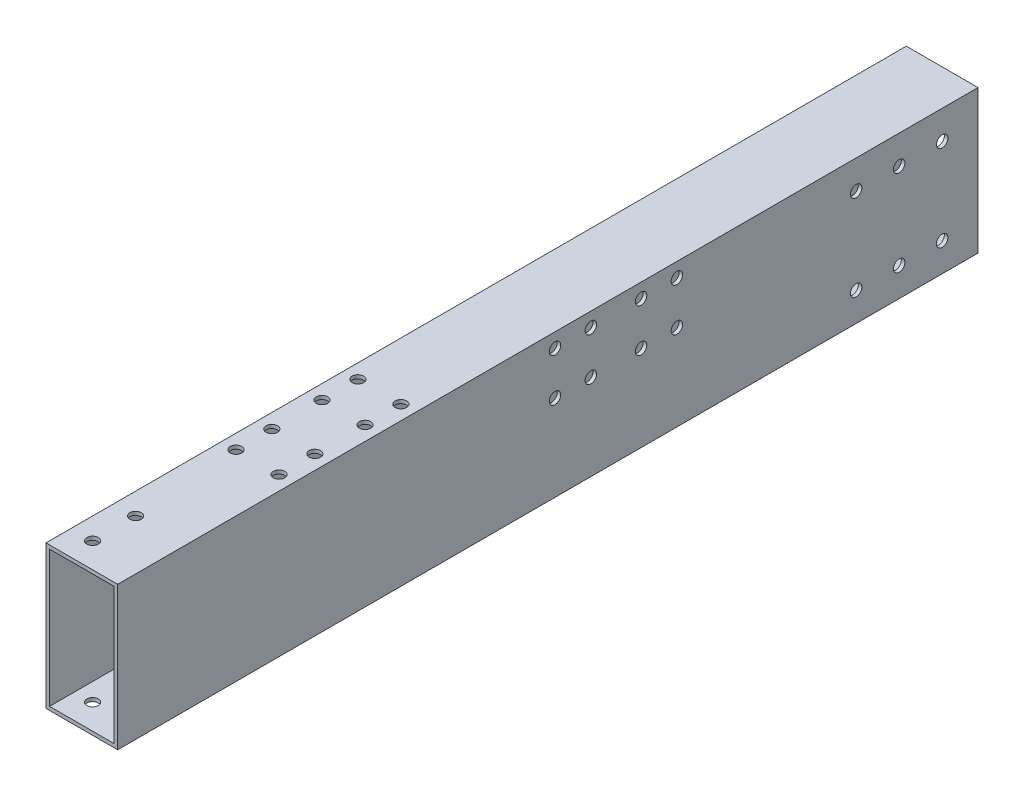
SolidWorks part; units mm, degrees
material "1060-O (SS)"
ref_plane "前视基准面" through (0, 0, 0) normal (0, 0, 1) x (1, 0, 0)
ref_plane "上视基准面" through (0, 0, 0) normal (0, 1, 0) x (1, 0, 0)
ref_plane "右视基准面" through (0, 0, 0) normal (1, 0, 0) x (0, 0, -1)
other "Configuration Table"
sketch "草图1" plane through (0, 0, 0) normal (0, 0, 1) x (1, 0, 0)
  line L1 (0, 0) -> (20, 0)
  line L2 (0, 0) -> (0, 40)
  line L3 (0, 40) -> (20, 40)
  line L4 (20, 0) -> (20, 40)
  line L5 (1, 1) -> (19, 1)
  line L6 (1, 1) -> (1, 39)
  line L7 (1, 39) -> (19, 39)
  line L8 (19, 1) -> (19, 39)
  dimension "D1" = 20
  dimension "D2" = 40
  dimension "D3" = 1
  dimension "D4" = 1
  dimension "D5" = 1
  dimension "D6" = 1
extrude "凸台-拉伸1" add sketch "草图1" along normal blind 240
sketch "草图2" plane through (0, 40, 0) normal (0, 1, 0) x (1, 0, 0)
  circle A1 centre (6, -221) radius 1.6
  circle A2 centre (6, -221) radius 1.6
  circle A3 centre (6, -233) radius 1.6
  circle A4 centre (6, -233) radius 1.6
  circle A21 centre (34, -221) radius 1.6
  circle A22 centre (34, -221) radius 1.6
  circle A23 centre (34, -233) radius 1.6
  circle A24 centre (34, -233) radius 1.6
  circle A25 centre (4, -191) radius 1.6
  circle A30 centre (4, -191) radius 1.6
  circle A31 centre (4, -181) radius 1.6
  circle A32 centre (4, -181) radius 1.6
  circle A33 centre (16, -167) radius 1.6
  circle A34 centre (16, -167) radius 1.6
  circle A35 centre (16, -157) radius 1.6
  circle A36 centre (16, -157) radius 1.6
  circle A37 centre (4, -167) radius 1.6
  circle A38 centre (4, -167) radius 1.6
  circle A39 centre (4, -157) radius 1.6
  circle A40 centre (4, -157) radius 1.6
  circle A41 centre (16, -191) radius 1.6
  circle A42 centre (16, -191) radius 1.6
  circle A43 centre (16, -181) radius 1.6
  circle A44 centre (16, -181) radius 1.6
  dimension "D1" = 0
  dimension "D2" = 0
  dimension "D7" = 0
  dimension "D8" = 0
  dimension "D9" = 0
  dimension "D10" = 0
  dimension "D11" = 0
  dimension "D12" = 0
  dimension "D13" = 0
  dimension "D14" = 0
  dimension "D15" = 0
  dimension "D16" = 0
extrude "切除-拉伸1" cut sketch "草图2" against normal blind 280
sketch "草图3" plane through (0, 0, 0) normal (-1, 0, 0) x (0, 0, 1)
  circle A1 centre (10, 8) radius 1.6
  circle A2 centre (10, 8) radius 1.6
  circle A3 centre (34, 8) radius 1.6
  circle A4 centre (34, 8) radius 1.6
  circle A5 centre (10, 32) radius 1.6
  circle A6 centre (10, 32) radius 1.6
  circle A7 centre (34, 32) radius 1.6
  circle A8 centre (34, 32) radius 1.6
  circle A25 centre (22, 32) radius 1.6
  circle A26 centre (22, 32) radius 1.6
  circle A27 centre (22, 8) radius 1.6
  circle A32 centre (22, 8) radius 1.6
  circle A33 centre (84, 24) radius 1.6
  circle A34 centre (84, 24) radius 1.6
  circle A35 centre (94, 24) radius 1.6
  circle A36 centre (94, 24) radius 1.6
  circle A37 centre (108, 36) radius 1.6
  circle A38 centre (108, 36) radius 1.6
  circle A39 centre (118, 36) radius 1.6
  circle A40 centre (118, 36) radius 1.6
  circle A41 centre (108, 24) radius 1.6
  circle A42 centre (108, 24) radius 1.6
  circle A43 centre (118, 24) radius 1.6
  circle A44 centre (118, 24) radius 1.6
  circle A45 centre (84, 36) radius 1.6
  circle A46 centre (84, 36) radius 1.6
  circle A47 centre (94, 36) radius 1.6
  circle A48 centre (94, 36) radius 1.6
  dimension "D1" = 0
  dimension "D2" = 0
  dimension "D3" = 0
  dimension "D4" = 0
  dimension "D9" = 0
  dimension "D10" = 0
  dimension "D11" = 0
  dimension "D12" = 0
  dimension "D13" = 0
  dimension "D14" = 0
  dimension "D15" = 0
  dimension "D16" = 0
  dimension "D17" = 0
  dimension "D18" = 0
extrude "切除-拉伸2" cut sketch "草图3" against normal blind 280
sketch "草图4" plane through (0, 40, 0) normal (0, 1, 0) x (1, 0, 0)
  line L0 (0, -215) -> (40, -215) construction
  line L1 (20, -240) -> (20, 0) construction
  line L2 (40, 0) -> (20, 0) construction
  circle A0 centre (10, -205) radius 6
  circle A1 centre (0, -19) radius 12.5
  circle A2 centre (0, -53) radius 12.5
  circle A3 centre (0, -87) radius 12.5
  circle A4 centre (0, -121) radius 12.5
  circle A7 centre (10, -185) radius 6
  circle A8 centre (10, -165) radius 6
  circle A9 centre (10, -145) radius 6
  dimension "D1" = 12
  dimension "D4" = 25
  dimension "D9" = 4
  dimension "D2" = 10
  dimension "D3" = 10
  dimension "D5" = 20
  dimension "D6" = 19
  dimension "D8" = 34
  dimension "D10" = 20
  dimension "D7" = 4
